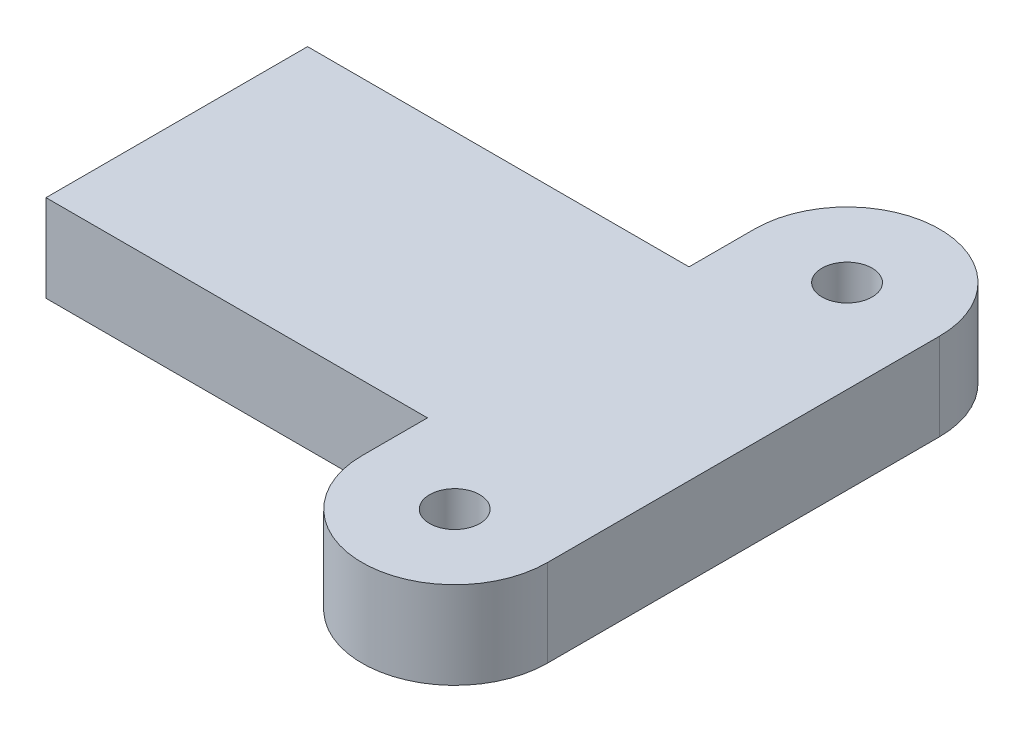
SolidWorks part; units mm, degrees
ref_plane "Plano frontal" through (0, 0, 0) normal (0, 0, 1) x (1, 0, 0)
ref_plane "Plano superior" through (0, 0, 0) normal (0, 1, 0) x (1, 0, 0)
ref_plane "Plano direito" through (0, 0, 0) normal (1, 0, 0) x (0, 0, -1)
sketch "Esboço1" plane through (0, 0, 0) normal (0, 1, 0) x (1, 0, 0)
  line L0 (0, 6) -> (0, -6)
  line L1 (0, 6) -> (-8.5, 6) construction
  line L2 (0, 6) -> (0, 9)
  line L3 (-8.5, 6) -> (-8.5, 9)
  line L4 (-4.25, 6) -> (-4.25, 9)
  line L5 (0, 0) -> (-8.5, 0) construction
  line L6 (0, -6) -> (-8.5, -6) construction
  line L7 (-4.25, -6) -> (-4.25, -9)
  line L8 (-8.5, -6) -> (-8.5, -9)
  line L9 (0, -6) -> (0, -9)
  line L10 (0, 6) -> (-26, 6) construction
  line L11 (0, 6) -> (-26, 6)
  line L12 (-26, 6) -> (-26, -6)
  line L13 (0, -6) -> (-26, -6) construction
  line L14 (0, -6) -> (-26, -6)
  circle A0 centre (-4.25, 9) radius 1.15
  arc A1 (0, 9) -> (-8.5, 9) centre (-4.25, 9) ccw
  arc A2 (0, -9) -> (-8.5, -9) centre (-4.25, -9) cw
  circle A3 centre (-4.25, -9) radius 1.15
  point P4 (0, 0)
  point P21 (-26, 0)
  dimension "D4" = 2.3
  dimension "D1" = 12
  dimension "D2" = 8.5
  dimension "D3" = 3
  dimension "D5" = 26
extrude "Ressalto-extrusão1" add sketch "Esboço1" along normal blind 4
